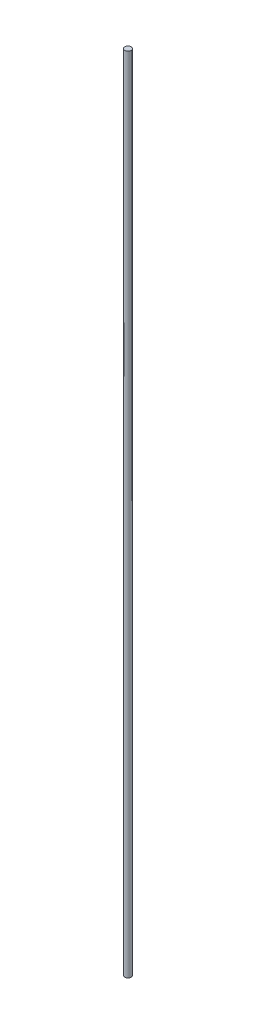
SolidWorks part; units mm, degrees
ref_plane "Front Plane" through (0, 0, 0) normal (0, 0, 1) x (1, 0, 0)
ref_plane "Top Plane" through (0, 0, 0) normal (0, 1, 0) x (1, 0, 0)
ref_plane "Right Plane" through (0, 0, 0) normal (1, 0, 0) x (0, 0, -1)
sketch "Sketch1" plane through (0, 0, 0) normal (0, 1, 0) x (1, 0, 0)
  circle A0 centre (0, 0) radius 4
  dimension "D1" = 8
extrude "Boss-Extrude1" add sketch "Sketch1" along normal blind 1010
